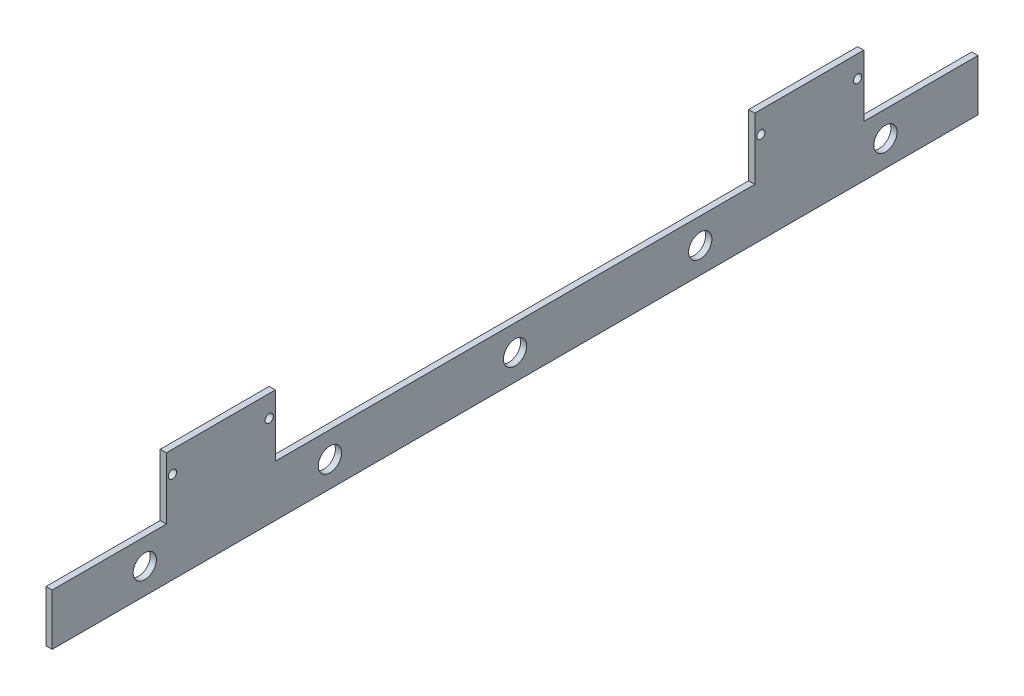
SolidWorks part; units mm, degrees
ref_plane "前视基准面" through (0, 0, 0) normal (0, 0, 1) x (1, 0, 0)
ref_plane "上视基准面" through (0, 0, 0) normal (0, 1, 0) x (1, 0, 0)
ref_plane "右视基准面" through (0, 0, 0) normal (1, 0, 0) x (0, 0, -1)
sketch "草图1" plane through (0, 0, 0) normal (1, 0, 0) x (0, 0, -1)
  line L1 (0, 0) -> (450, 0)
  line L2 (0, 0) -> (0, 25)
  line L3 (0, 25) -> (450, 25)
  line L4 (450, 0) -> (450, 25)
  dimension "D1" = 450
  dimension "D2" = 25
extrude "凸台-拉伸1" add sketch "草图1" along normal blind 3
sketch "草图2" plane through (3, 0, 0) normal (1, 0, 0) x (0, 0, -1)
  line L0 (225, 0) -> (225, 25) construction
  line L1 (0, 0) -> (450, 0) construction
  line L2 (450, 25) -> (0, 25) construction
  line L3 (82, 25) -> (82, 55) construction
  line L4 (55.5, 25) -> (108.5, 25)
  line L5 (55.5, 25) -> (55.5, 55)
  line L6 (55.5, 55) -> (108.5, 55)
  line L7 (108.5, 25) -> (108.5, 55)
  line L8 (341.5, 25) -> (341.5, 55)
  line L9 (394.5, 55) -> (341.5, 55)
  line L10 (394.5, 25) -> (394.5, 55)
  line L11 (394.5, 25) -> (341.5, 25)
  circle A0 centre (58.5, 44.5) radius 2
  circle A1 centre (105.5, 44.5) radius 2
  circle A2 centre (344.5, 44.5) radius 2
  circle A3 centre (391.5, 44.5) radius 2
  dimension "D2" = 239
  dimension "D3" = 333
  dimension "D4" = 4
  dimension "D1" = 53
  dimension "D5" = 10.5
  dimension "D6" = 30
extrude "凸台-拉伸2" add sketch "草图2" against normal blind 3
sketch "草图3" plane through (3, 0, 0) normal (1, 0, 0) x (0, 0, -1)
  line L0 (225, 25) -> (225, 0) construction
  line L1 (341.5, 25) -> (108.5, 25) construction
  line L2 (0, 0) -> (450, 0) construction
  circle A0 centre (225, 12.5) radius 5.655
  circle A1 centre (315, 12.5) radius 5.655
  circle A2 centre (405, 12.5) radius 5.655
  circle A3 centre (135, 12.5) radius 5.655
  circle A4 centre (45, 12.5) radius 5.655
  dimension "D1" = 3
  dimension "D2" = 3
extrude "切除-拉伸1" cut sketch "草图3" against normal through all
